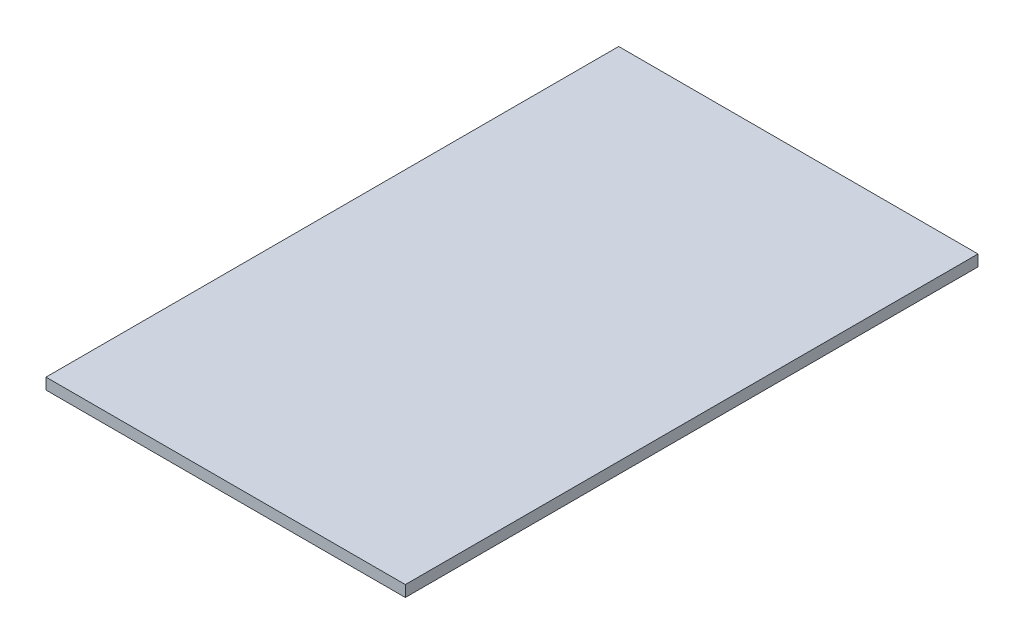
SolidWorks part; units mm, degrees
ref_plane "Front Plane" through (0, 0, 0) normal (0, 0, 1) x (1, 0, 0)
ref_plane "Top Plane" through (0, 0, 0) normal (0, 1, 0) x (1, 0, 0)
ref_plane "Right Plane" through (0, 0, 0) normal (1, 0, 0) x (0, 0, -1)
sketch "Sketch1" plane through (0, 0, 0) normal (0, 1, 0) x (1, 0, 0)
  line L1 (-29.5015, 280.4456) -> (173.6985, 280.4456)
  line L2 (-29.5015, 280.4456) -> (-29.5015, -43.4044)
  line L3 (-29.5015, -43.4044) -> (173.6985, -43.4044)
  line L4 (173.6985, 280.4456) -> (173.6985, -43.4044)
  dimension "D1" = 323.85
  dimension "D2" = 203.2
extrude "Boss-Extrude1" add sketch "Sketch1" along normal blind 6.35
